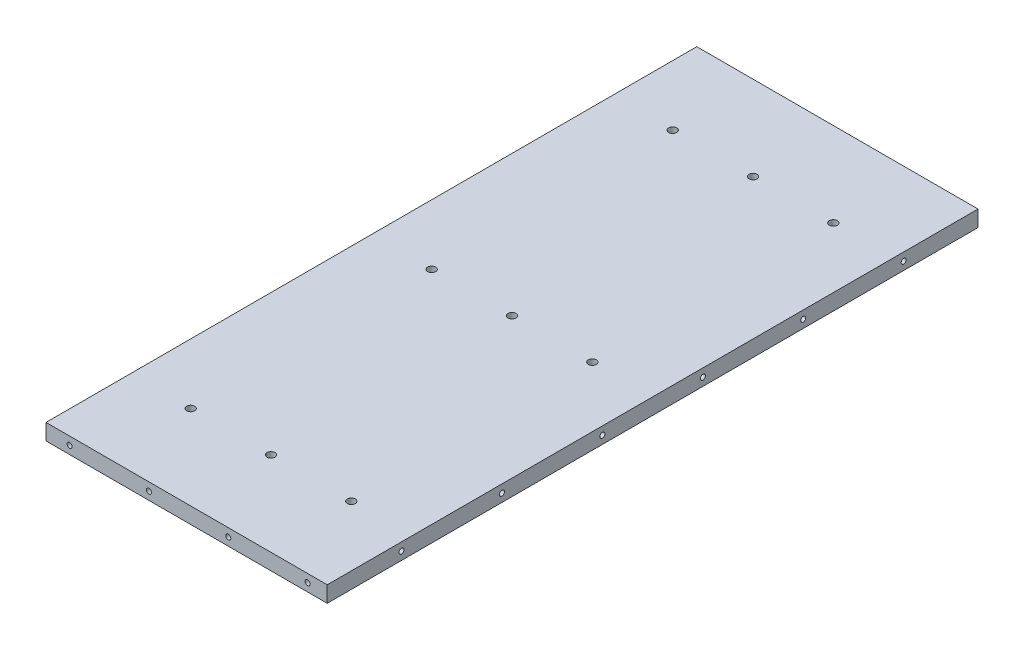
SolidWorks part; units mm, degrees
ref_plane "Front Plane" through (0, 0, 0) normal (0, 0, 1) x (1, 0, 0)
ref_plane "Top Plane" through (0, 0, 0) normal (0, 1, 0) x (1, 0, 0)
ref_plane "Right Plane" through (0, 0, 0) normal (1, 0, 0) x (0, 0, -1)
sketch "Sketch1" plane through (0, 0, 0) normal (0, 1, 0) x (1, 0, 0)
  line L1 (70, -162) -> (-70, -162)
  line L2 (70, -162) -> (70, 162)
  line L3 (70, 162) -> (-70, 162)
  line L4 (-70, -162) -> (-70, 162)
  line L5 (70, -162) -> (-70, 162) construction
  line L6 (70, 162) -> (-70, -162) construction
  point P0 (0, 0)
  dimension "D1" = 324
  dimension "D2" = 140
extrude "Boss-Extrude1" add sketch "Sketch1" along normal blind 8
sketch "Sketch2" plane through (0, 0, 162) normal (0, 0, 1) x (1, 0, 0)
  point P0 (60.25, 4)
  point P2 (20.75, 4)
  point P4 (-18.75, 4)
  point P6 (-58.25, 4)
  point P8 (-78, 4)
  point P10 (-78, 4)
  point P12 (-78, 4)
  point P14 (-78, 4)
  point P16 (-78, 4)
  point P18 (-78, 4)
hole_wizard "M3x0.5 Tapped Hole1" positions "Sketch3" profile "Sketch5" tap size "M3x0.5" standard "BSI"
sketch "Sketch3" plane through (0, 0, 162) normal (0, 0, 1) x (1, 0, 0)
  point P0 (60.25, 4)
  point P3 (20.75, 4)
  point P6 (-18.75, 4)
  point P9 (-58.25, 4)
sketch "Sketch5" plane through (60.25, 4, 162) normal (1, 0, 0) x (0, -1, 0)
  line L0 (0, 0) -> (0, 12.2511)
  line L1 (0, 12.2511) -> (1.25, 11.5)
  line L2 (1.25, 11.5) -> (1.25, 0)
  line L5 (1.25, 0) -> (0, 0)
  line L10 (0, 12.2511) -> (-1.25, 11.5) construction
  line L11 (0, -6.35) -> (0, 107.95) construction
  dimension "Tap Drill Dia." = 2.5
  dimension "Tap Drill Depth" = 11.5
  dimension "Drill Angle" = 118
cosmetic thread "Hole Thread1" parameters "D1"=10, "D2"=3
cosmetic thread "Hole Thread2" parameters "D1"=10, "D2"=3
cosmetic thread "Hole Thread3" parameters "D1"=10, "D2"=3
cosmetic thread "Hole Thread4" parameters "D1"=10, "D2"=3
sketch "Sketch6" plane through (-70, 0, 0) normal (-1, 0, 0) x (0, 0, 1)
  line L0 (-125, 4) -> (-75, 4) construction
  line L1 (-75, 4) -> (-25, 4) construction
  line L2 (-25, 4) -> (25, 4) construction
  line L3 (25, 4) -> (75, 4) construction
  line L4 (75, 4) -> (125, 4) construction
  line L5 (0, 8) -> (0, 0) construction
  line L6 (-162, 8) -> (162, 8) construction
  point P0 (125, 4)
  point P2 (75, 4)
  point P4 (25, 4)
  point P6 (-25, 4)
  point P8 (-75, 4)
  point P10 (-125, 4)
  dimension "D1" = 50
  dimension "D2" = 25
  dimension "D3" = 50
  dimension "D4" = 50
  dimension "D5" = 50
  dimension "D6" = 50
hole_wizard "M3x0.5 Tapped Hole2" positions "3DSketch1" profile "Sketch7" tap size "M3x0.5" standard "BSI"
sketch3d "3DSketch1"
  point P0 (-70, 4, -125)
  point P3 (-70, 4, -75)
  point P6 (-70, 4, -25)
  point P9 (-70, 4, 25)
  point P12 (-70, 4, 75)
  point P15 (-70, 4, 125)
sketch "Sketch7" plane through (-70, 4, -125) normal (0, 1, 0) x (0, 0, 1)
  line L0 (0, 0) -> (0, 12.2511)
  line L1 (0, 12.2511) -> (1.25, 11.5)
  line L2 (1.25, 11.5) -> (1.25, 0)
  line L5 (1.25, 0) -> (0, 0)
  line L10 (0, 12.2511) -> (-1.25, 11.5) construction
  line L11 (0, -6.35) -> (0, 107.95) construction
  dimension "Tap Drill Dia." = 2.5
  dimension "Tap Drill Depth" = 11.5
  dimension "Drill Angle" = 118
cosmetic thread "Hole Thread5" parameters "D1"=10, "D2"=3
cosmetic thread "Hole Thread6" parameters "D1"=10, "D2"=3
cosmetic thread "Hole Thread7" parameters "D1"=10, "D2"=3
cosmetic thread "Hole Thread8" parameters "D1"=10, "D2"=3
cosmetic thread "Hole Thread9" parameters "D1"=10, "D2"=3
cosmetic thread "Hole Thread10" parameters "D1"=10, "D2"=3
mirror "Mirror1" about plane through (0, 0, 0) normal (0, 0, 1) of "M3x0.5 Tapped Hole1"
mirror "Mirror2" about plane through (0, 0, 0) normal (1, 0, 0) of "M3x0.5 Tapped Hole2"
sketch "Sketch8" plane through (0, 8, 0) normal (0, 1, 0) x (1, 0, 0)
  point P0 (-40, 0)
  dimension "D1" = 40
hole_wizard "Ø4.0mm Dowel Hole1" positions "3DSketch2" profile "Sketch9" hole size "Ø4.0" standard "BSI"
sketch3d "3DSketch2"
  point P0 (-40, 8, 0)
sketch "Sketch9" plane through (-40, 8, 0) normal (1, 0, 0) x (0, 0, 1)
  line L0 (0, 0) -> (0, 11.2017)
  line L1 (0, 11.2017) -> (2, 10)
  line L2 (2, 10) -> (2, 0)
  line L5 (2, 0) -> (0, 0)
  line L10 (0, 11.2017) -> (-2, 10) construction
  line L11 (0, -6.35) -> (0, 107.95) construction
  dimension "Hole Dia." = 4
  dimension "Hole Depth" = 10
  dimension "Drill Angle" = 118
pattern_linear "LPattern1" count 3 spacing 40 along (1, 0, 0) count 2 spacing 120 along (0, 0, 1) of "Ø4.0mm Dowel Hole1"
mirror "Mirror3" about plane through (0, 0, 0) normal (0, 0, 1) of "LPattern1"
